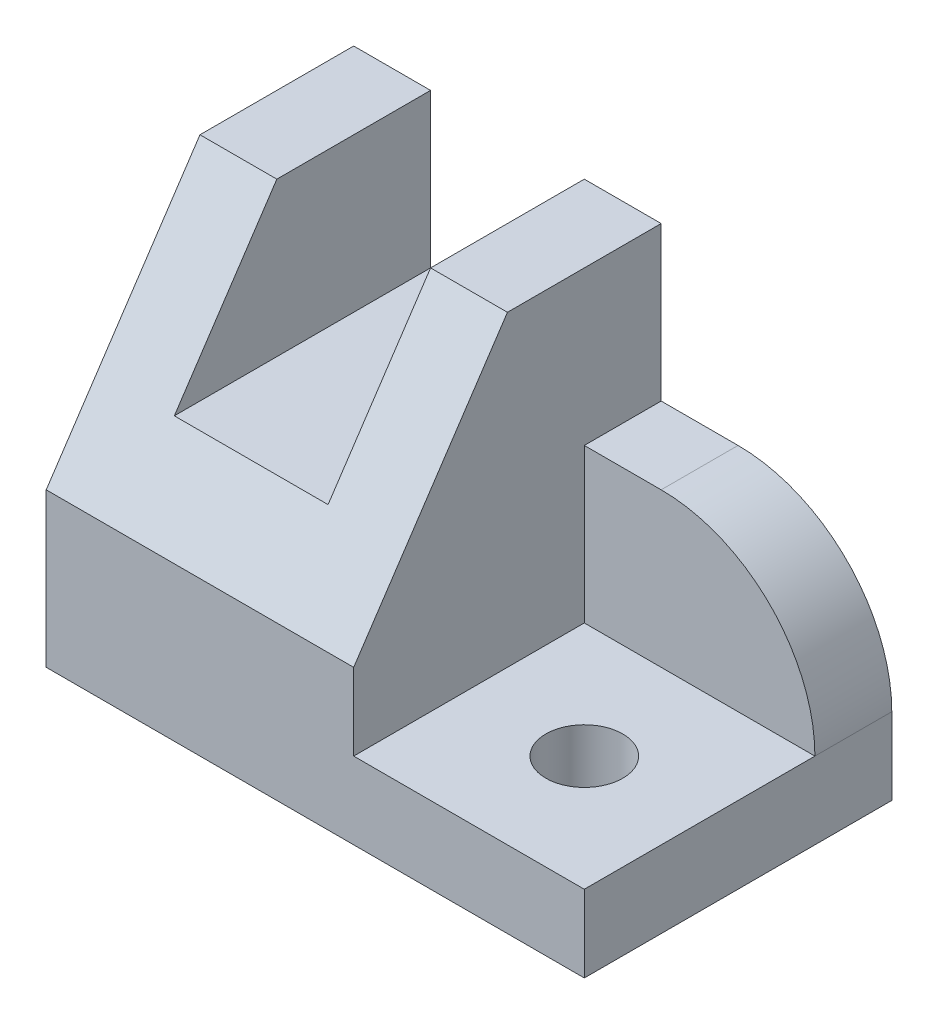
SolidWorks part; units mm, degrees
ref_plane "前基準面" through (0, 0, 0) normal (0, 0, 1) x (1, 0, 0)
ref_plane "上基準面" through (0, 0, 0) normal (0, 1, 0) x (1, 0, 0)
ref_plane "右基準面" through (0, 0, 0) normal (1, 0, 0) x (0, 0, -1)
sketch "草圖1" plane through (0, 0, 0) normal (1, 0, 0) x (0, 0, -1)
  line L0 (-10, 20) -> (-20, 5)
  line L1 (0, 0) -> (-20, 0)
  line L2 (0, 0) -> (0, 20)
  line L3 (0, 20) -> (-10, 20)
  line L4 (-20, 0) -> (-20, 5)
  point P1 (0, 0)
  dimension "D1" = 10
  dimension "D2" = 5
  dimension "D3" = 20
  dimension "D4" = 20
extrude "填料-伸長1" add sketch "草圖1" along normal blind 20
sketch "草圖3" plane through (0, 0, 0) normal (0, -1, 0) x (1, 0, 0)
  line L1 (0, 0) -> (35, 0)
  line L2 (0, 0) -> (0, 20)
  line L3 (0, 20) -> (35, 20)
  line L4 (35, 0) -> (35, 20)
  dimension "D1" = 35
  dimension "D2" = 20
extrude "填料-伸長2" add sketch "草圖3" along normal blind 5
sketch "草圖4" plane through (0, 0, 0) normal (0, 0, -1) x (-1, 0, 0)
  line L0 (-35, -5) -> (-35, 0) construction
  line L1 (-20, 0) -> (-35, 0)
  line L2 (-20, 0) -> (-20, 10)
  line L3 (-20, 10) -> (-35, 10)
  line L4 (-35, 0) -> (-35, 10)
  dimension "D1" = 15
  dimension "D2" = 10
extrude "填料-伸長3" add sketch "草圖4" against normal blind 5
fillet "圓角1" radius 10 1 edges at (35, 10, 2.5)
sketch "草圖5" plane through (0, 0, 0) normal (0, 0, 1) x (1, 0, 0)
  line L0 (20, 20) -> (0, 20) construction
  line L1 (5, 30) -> (15, 30)
  line L2 (5, 30) -> (5, 10)
  line L3 (5, 10) -> (15, 10)
  line L4 (15, 30) -> (15, 10)
  line L5 (5, 30) -> (15, 10) construction
  line L6 (5, 10) -> (15, 30) construction
  point P0 (10, 20)
  dimension "D1" = 10
  dimension "D2" = 10
extrude "除料-伸長1" cut sketch "草圖5" along normal through all both and the other way through all
sketch "草圖6" plane through (0, 0, 0) normal (0, 1, 0) x (1, 0, 0)
  line L2 (20, -10) -> (39.1367, -10) construction
  line L4 (35, -5) -> (35, -20) construction
  circle A0 centre (27.5, -12.5) radius 2.5
  dimension "D1" = 5
  dimension "D2" = 7.5
extrude "除料-伸長2" cut sketch "草圖6" against normal blind 5
